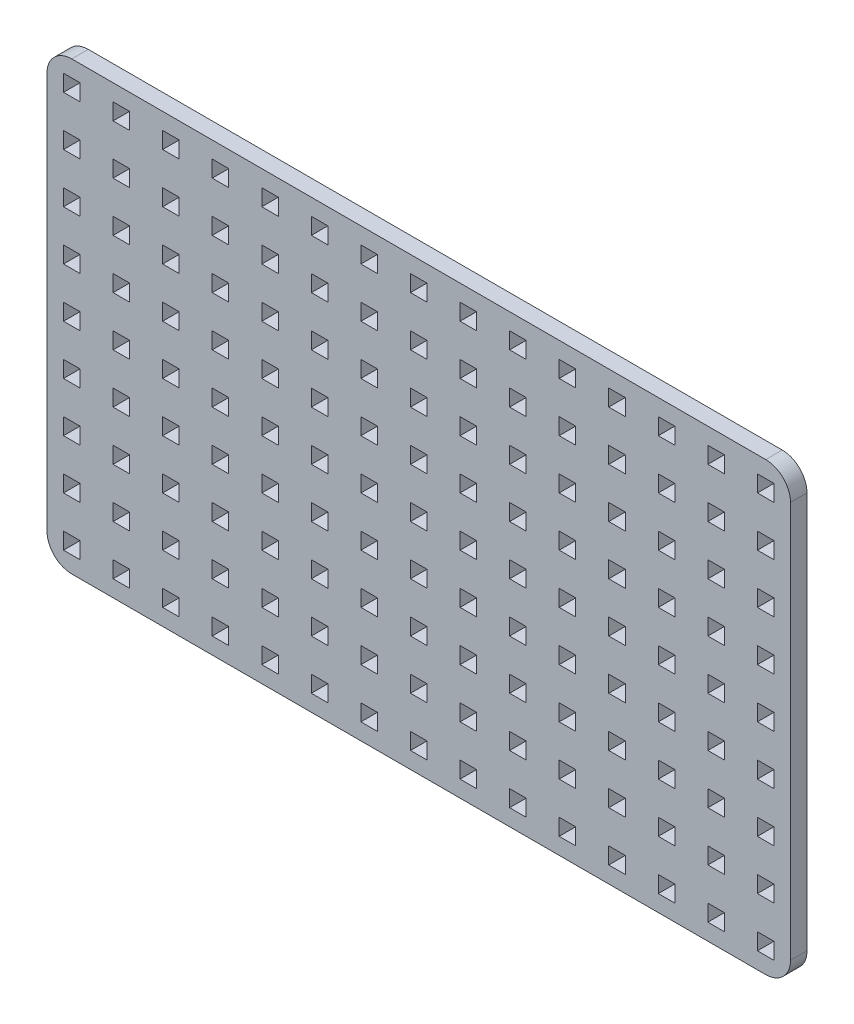
SolidWorks part; units mm, degrees
ref_plane "Alzado" through (0, 0, 0) normal (0, 0, 1) x (1, 0, 0)
ref_plane "Planta" through (0, 0, 0) normal (0, 1, 0) x (1, 0, 0)
ref_plane "Vista lateral" through (0, 0, 0) normal (1, 0, 0) x (0, 0, -1)
sketch "Model" plane through (0, 0, 0) normal (0, 0, 1) x (1, 0, 0)
  line L0 (12.5036, 293.2506) -> (12.5036, 290.2506)
  line L1 (15.5036, 293.2506) -> (12.5036, 293.2506)
  line L2 (15.5036, 290.2506) -> (15.5036, 293.2506)
  line L3 (12.5036, 290.2506) -> (15.5036, 290.2506)
  line L4 (21.5036, 293.2506) -> (21.5036, 290.2506)
  line L5 (24.5036, 293.2506) -> (21.5036, 293.2506)
  line L6 (24.5036, 290.2506) -> (24.5036, 293.2506)
  line L7 (21.5036, 290.2506) -> (24.5036, 290.2506)
  line L8 (30.5036, 293.2506) -> (30.5036, 290.2506)
  line L9 (33.5036, 293.2506) -> (30.5036, 293.2506)
  line L10 (33.5036, 290.2506) -> (33.5036, 293.2506)
  line L11 (30.5036, 290.2506) -> (33.5036, 290.2506)
  line L12 (39.5036, 293.2506) -> (39.5036, 290.2506)
  line L13 (42.5036, 293.2506) -> (39.5036, 293.2506)
  line L14 (42.5036, 290.2506) -> (42.5036, 293.2506)
  line L15 (39.5036, 290.2506) -> (42.5036, 290.2506)
  line L16 (48.5036, 293.2506) -> (48.5036, 290.2506)
  line L17 (51.5036, 293.2506) -> (48.5036, 293.2506)
  line L18 (51.5036, 290.2506) -> (51.5036, 293.2506)
  line L19 (48.5036, 290.2506) -> (51.5036, 290.2506)
  line L20 (57.5036, 293.2506) -> (57.5036, 290.2506)
  line L21 (60.5036, 293.2506) -> (57.5036, 293.2506)
  line L22 (60.5036, 290.2506) -> (60.5036, 293.2506)
  line L23 (57.5036, 290.2506) -> (60.5036, 290.2506)
  line L24 (66.5036, 293.2506) -> (66.5036, 290.2506)
  line L25 (69.5036, 293.2506) -> (66.5036, 293.2506)
  line L26 (69.5036, 290.2506) -> (69.5036, 293.2506)
  line L27 (66.5036, 290.2506) -> (69.5036, 290.2506)
  line L28 (75.5036, 293.2506) -> (75.5036, 290.2506)
  line L29 (78.5036, 293.2506) -> (75.5036, 293.2506)
  line L30 (78.5036, 290.2506) -> (78.5036, 293.2506)
  line L31 (75.5036, 290.2506) -> (78.5036, 290.2506)
  line L32 (84.5036, 293.2506) -> (84.5036, 290.2506)
  line L33 (87.5036, 293.2506) -> (84.5036, 293.2506)
  line L34 (87.5036, 290.2506) -> (87.5036, 293.2506)
  line L35 (84.5036, 290.2506) -> (87.5036, 290.2506)
  line L36 (93.5036, 293.2506) -> (93.5036, 290.2506)
  line L37 (96.5036, 293.2506) -> (93.5036, 293.2506)
  line L38 (96.5036, 290.2506) -> (96.5036, 293.2506)
  line L39 (93.5036, 290.2506) -> (96.5036, 290.2506)
  line L40 (102.5036, 293.2506) -> (102.5036, 290.2506)
  line L41 (105.5036, 293.2506) -> (102.5036, 293.2506)
  line L42 (105.5036, 290.2506) -> (105.5036, 293.2506)
  line L43 (102.5036, 290.2506) -> (105.5036, 290.2506)
  line L44 (111.5036, 293.2506) -> (111.5036, 290.2506)
  line L45 (114.5036, 293.2506) -> (111.5036, 293.2506)
  line L46 (114.5036, 290.2506) -> (114.5036, 293.2506)
  line L47 (111.5036, 290.2506) -> (114.5036, 290.2506)
  line L48 (120.5036, 293.2506) -> (120.5036, 290.2506)
  line L49 (123.5036, 293.2506) -> (120.5036, 293.2506)
  line L50 (123.5036, 290.2506) -> (123.5036, 293.2506)
  line L51 (120.5036, 290.2506) -> (123.5036, 290.2506)
  line L52 (129.5036, 293.2506) -> (129.5036, 290.2506)
  line L53 (132.5036, 293.2506) -> (129.5036, 293.2506)
  line L54 (132.5036, 290.2506) -> (132.5036, 293.2506)
  line L55 (129.5036, 290.2506) -> (132.5036, 290.2506)
  line L56 (138.5036, 293.2506) -> (138.5036, 290.2506)
  line L57 (141.5036, 293.2506) -> (138.5036, 293.2506)
  line L58 (141.5036, 290.2506) -> (141.5036, 293.2506)
  line L59 (138.5036, 290.2506) -> (141.5036, 290.2506)
  line L60 (12.5036, 284.2506) -> (12.5036, 281.2506)
  line L61 (15.5036, 284.2506) -> (12.5036, 284.2506)
  line L62 (15.5036, 281.2506) -> (15.5036, 284.2506)
  line L63 (12.5036, 281.2506) -> (15.5036, 281.2506)
  line L64 (21.5036, 284.2506) -> (21.5036, 281.2506)
  line L65 (24.5036, 284.2506) -> (21.5036, 284.2506)
  line L66 (24.5036, 281.2506) -> (24.5036, 284.2506)
  line L67 (21.5036, 281.2506) -> (24.5036, 281.2506)
  line L68 (30.5036, 284.2506) -> (30.5036, 281.2506)
  line L69 (33.5036, 284.2506) -> (30.5036, 284.2506)
  line L70 (33.5036, 281.2506) -> (33.5036, 284.2506)
  line L71 (30.5036, 281.2506) -> (33.5036, 281.2506)
  line L72 (39.5036, 284.2506) -> (39.5036, 281.2506)
  line L73 (42.5036, 284.2506) -> (39.5036, 284.2506)
  line L74 (42.5036, 281.2506) -> (42.5036, 284.2506)
  line L75 (39.5036, 281.2506) -> (42.5036, 281.2506)
  line L76 (48.5036, 284.2506) -> (48.5036, 281.2506)
  line L77 (51.5036, 284.2506) -> (48.5036, 284.2506)
  line L78 (51.5036, 281.2506) -> (51.5036, 284.2506)
  line L79 (48.5036, 281.2506) -> (51.5036, 281.2506)
  line L80 (57.5036, 284.2506) -> (57.5036, 281.2506)
  line L81 (60.5036, 284.2506) -> (57.5036, 284.2506)
  line L82 (60.5036, 281.2506) -> (60.5036, 284.2506)
  line L83 (57.5036, 281.2506) -> (60.5036, 281.2506)
  line L84 (66.5036, 284.2506) -> (66.5036, 281.2506)
  line L85 (69.5036, 284.2506) -> (66.5036, 284.2506)
  line L86 (69.5036, 281.2506) -> (69.5036, 284.2506)
  line L87 (66.5036, 281.2506) -> (69.5036, 281.2506)
  line L88 (75.5036, 284.2506) -> (75.5036, 281.2506)
  line L89 (78.5036, 284.2506) -> (75.5036, 284.2506)
  line L90 (78.5036, 281.2506) -> (78.5036, 284.2506)
  line L91 (75.5036, 281.2506) -> (78.5036, 281.2506)
  line L92 (84.5036, 284.2506) -> (84.5036, 281.2506)
  line L93 (87.5036, 284.2506) -> (84.5036, 284.2506)
  line L94 (87.5036, 281.2506) -> (87.5036, 284.2506)
  line L95 (84.5036, 281.2506) -> (87.5036, 281.2506)
  line L96 (93.5036, 284.2506) -> (93.5036, 281.2506)
  line L97 (96.5036, 284.2506) -> (93.5036, 284.2506)
  line L98 (96.5036, 281.2506) -> (96.5036, 284.2506)
  line L99 (93.5036, 281.2506) -> (96.5036, 281.2506)
  line L100 (102.5036, 284.2506) -> (102.5036, 281.2506)
  line L101 (105.5036, 284.2506) -> (102.5036, 284.2506)
  line L102 (105.5036, 281.2506) -> (105.5036, 284.2506)
  line L103 (102.5036, 281.2506) -> (105.5036, 281.2506)
  line L104 (111.5036, 284.2506) -> (111.5036, 281.2506)
  line L105 (114.5036, 284.2506) -> (111.5036, 284.2506)
  line L106 (114.5036, 281.2506) -> (114.5036, 284.2506)
  line L107 (111.5036, 281.2506) -> (114.5036, 281.2506)
  line L108 (120.5036, 284.2506) -> (120.5036, 281.2506)
  line L109 (123.5036, 284.2506) -> (120.5036, 284.2506)
  line L110 (123.5036, 281.2506) -> (123.5036, 284.2506)
  line L111 (120.5036, 281.2506) -> (123.5036, 281.2506)
  line L112 (129.5036, 284.2506) -> (129.5036, 281.2506)
  line L113 (132.5036, 284.2506) -> (129.5036, 284.2506)
  line L114 (132.5036, 281.2506) -> (132.5036, 284.2506)
  line L115 (129.5036, 281.2506) -> (132.5036, 281.2506)
  line L116 (138.5036, 284.2506) -> (138.5036, 281.2506)
  line L117 (141.5036, 284.2506) -> (138.5036, 284.2506)
  line L118 (141.5036, 281.2506) -> (141.5036, 284.2506)
  line L119 (138.5036, 281.2506) -> (141.5036, 281.2506)
  line L120 (12.5036, 275.2506) -> (12.5036, 272.2506)
  line L121 (15.5036, 275.2506) -> (12.5036, 275.2506)
  line L122 (15.5036, 272.2506) -> (15.5036, 275.2506)
  line L123 (12.5036, 272.2506) -> (15.5036, 272.2506)
  line L124 (21.5036, 275.2506) -> (21.5036, 272.2506)
  line L125 (24.5036, 275.2506) -> (21.5036, 275.2506)
  line L126 (24.5036, 272.2506) -> (24.5036, 275.2506)
  line L127 (21.5036, 272.2506) -> (24.5036, 272.2506)
  line L128 (30.5036, 275.2506) -> (30.5036, 272.2506)
  line L129 (33.5036, 275.2506) -> (30.5036, 275.2506)
  line L130 (33.5036, 272.2506) -> (33.5036, 275.2506)
  line L131 (30.5036, 272.2506) -> (33.5036, 272.2506)
  line L132 (39.5036, 275.2506) -> (39.5036, 272.2506)
  line L133 (42.5036, 275.2506) -> (39.5036, 275.2506)
  line L134 (42.5036, 272.2506) -> (42.5036, 275.2506)
  line L135 (39.5036, 272.2506) -> (42.5036, 272.2506)
  line L136 (48.5036, 275.2506) -> (48.5036, 272.2506)
  line L137 (51.5036, 275.2506) -> (48.5036, 275.2506)
  line L138 (51.5036, 272.2506) -> (51.5036, 275.2506)
  line L139 (48.5036, 272.2506) -> (51.5036, 272.2506)
  line L140 (57.5036, 275.2506) -> (57.5036, 272.2506)
  line L141 (60.5036, 275.2506) -> (57.5036, 275.2506)
  line L142 (60.5036, 272.2506) -> (60.5036, 275.2506)
  line L143 (57.5036, 272.2506) -> (60.5036, 272.2506)
  line L144 (66.5036, 275.2506) -> (66.5036, 272.2506)
  line L145 (69.5036, 275.2506) -> (66.5036, 275.2506)
  line L146 (69.5036, 272.2506) -> (69.5036, 275.2506)
  line L147 (66.5036, 272.2506) -> (69.5036, 272.2506)
  line L148 (75.5036, 275.2506) -> (75.5036, 272.2506)
  line L149 (78.5036, 275.2506) -> (75.5036, 275.2506)
  line L150 (78.5036, 272.2506) -> (78.5036, 275.2506)
  line L151 (75.5036, 272.2506) -> (78.5036, 272.2506)
  line L152 (84.5036, 275.2506) -> (84.5036, 272.2506)
  line L153 (87.5036, 275.2506) -> (84.5036, 275.2506)
  line L154 (87.5036, 272.2506) -> (87.5036, 275.2506)
  line L155 (84.5036, 272.2506) -> (87.5036, 272.2506)
  line L156 (93.5036, 275.2506) -> (93.5036, 272.2506)
  line L157 (96.5036, 275.2506) -> (93.5036, 275.2506)
  line L158 (96.5036, 272.2506) -> (96.5036, 275.2506)
  line L159 (93.5036, 272.2506) -> (96.5036, 272.2506)
  line L160 (102.5036, 275.2506) -> (102.5036, 272.2506)
  line L161 (105.5036, 275.2506) -> (102.5036, 275.2506)
  line L162 (105.5036, 272.2506) -> (105.5036, 275.2506)
  line L163 (102.5036, 272.2506) -> (105.5036, 272.2506)
  line L164 (111.5036, 275.2506) -> (111.5036, 272.2506)
  line L165 (114.5036, 275.2506) -> (111.5036, 275.2506)
  line L166 (114.5036, 272.2506) -> (114.5036, 275.2506)
  line L167 (111.5036, 272.2506) -> (114.5036, 272.2506)
  line L168 (120.5036, 275.2506) -> (120.5036, 272.2506)
  line L169 (123.5036, 275.2506) -> (120.5036, 275.2506)
  line L170 (123.5036, 272.2506) -> (123.5036, 275.2506)
  line L171 (120.5036, 272.2506) -> (123.5036, 272.2506)
  line L172 (129.5036, 275.2506) -> (129.5036, 272.2506)
  line L173 (132.5036, 275.2506) -> (129.5036, 275.2506)
  line L174 (132.5036, 272.2506) -> (132.5036, 275.2506)
  line L175 (129.5036, 272.2506) -> (132.5036, 272.2506)
  line L176 (138.5036, 275.2506) -> (138.5036, 272.2506)
  line L177 (141.5036, 275.2506) -> (138.5036, 275.2506)
  line L178 (141.5036, 272.2506) -> (141.5036, 275.2506)
  line L179 (138.5036, 272.2506) -> (141.5036, 272.2506)
  line L180 (12.5036, 266.2506) -> (12.5036, 263.2506)
  line L181 (15.5036, 266.2506) -> (12.5036, 266.2506)
  line L182 (15.5036, 263.2506) -> (15.5036, 266.2506)
  line L183 (12.5036, 263.2506) -> (15.5036, 263.2506)
  line L184 (21.5036, 266.2506) -> (21.5036, 263.2506)
  line L185 (24.5036, 266.2506) -> (21.5036, 266.2506)
  line L186 (24.5036, 263.2506) -> (24.5036, 266.2506)
  line L187 (21.5036, 263.2506) -> (24.5036, 263.2506)
  line L188 (30.5036, 266.2506) -> (30.5036, 263.2506)
  line L189 (33.5036, 266.2506) -> (30.5036, 266.2506)
  line L190 (33.5036, 263.2506) -> (33.5036, 266.2506)
  line L191 (30.5036, 263.2506) -> (33.5036, 263.2506)
  line L192 (39.5036, 266.2506) -> (39.5036, 263.2506)
  line L193 (42.5036, 266.2506) -> (39.5036, 266.2506)
  line L194 (42.5036, 263.2506) -> (42.5036, 266.2506)
  line L195 (39.5036, 263.2506) -> (42.5036, 263.2506)
  line L196 (48.5036, 266.2506) -> (48.5036, 263.2506)
  line L197 (51.5036, 266.2506) -> (48.5036, 266.2506)
  line L198 (51.5036, 263.2506) -> (51.5036, 266.2506)
  line L199 (48.5036, 263.2506) -> (51.5036, 263.2506)
  line L200 (57.5036, 266.2506) -> (57.5036, 263.2506)
  line L201 (60.5036, 266.2506) -> (57.5036, 266.2506)
  line L202 (60.5036, 263.2506) -> (60.5036, 266.2506)
  line L203 (57.5036, 263.2506) -> (60.5036, 263.2506)
  line L204 (66.5036, 266.2506) -> (66.5036, 263.2506)
  line L205 (69.5036, 266.2506) -> (66.5036, 266.2506)
  line L206 (69.5036, 263.2506) -> (69.5036, 266.2506)
  line L207 (66.5036, 263.2506) -> (69.5036, 263.2506)
  line L208 (75.5036, 266.2506) -> (75.5036, 263.2506)
  line L209 (78.5036, 266.2506) -> (75.5036, 266.2506)
  line L210 (78.5036, 263.2506) -> (78.5036, 266.2506)
  line L211 (75.5036, 263.2506) -> (78.5036, 263.2506)
  line L212 (84.5036, 266.2506) -> (84.5036, 263.2506)
  line L213 (87.5036, 266.2506) -> (84.5036, 266.2506)
  line L214 (87.5036, 263.2506) -> (87.5036, 266.2506)
  line L215 (84.5036, 263.2506) -> (87.5036, 263.2506)
  line L216 (93.5036, 266.2506) -> (93.5036, 263.2506)
  line L217 (96.5036, 266.2506) -> (93.5036, 266.2506)
  line L218 (96.5036, 263.2506) -> (96.5036, 266.2506)
  line L219 (93.5036, 263.2506) -> (96.5036, 263.2506)
  line L220 (102.5036, 266.2506) -> (102.5036, 263.2506)
  line L221 (105.5036, 266.2506) -> (102.5036, 266.2506)
  line L222 (105.5036, 263.2506) -> (105.5036, 266.2506)
  line L223 (102.5036, 263.2506) -> (105.5036, 263.2506)
  line L224 (111.5036, 266.2506) -> (111.5036, 263.2506)
  line L225 (114.5036, 266.2506) -> (111.5036, 266.2506)
  line L226 (114.5036, 263.2506) -> (114.5036, 266.2506)
  line L227 (111.5036, 263.2506) -> (114.5036, 263.2506)
  line L228 (120.5036, 266.2506) -> (120.5036, 263.2506)
  line L229 (123.5036, 266.2506) -> (120.5036, 266.2506)
  line L230 (123.5036, 263.2506) -> (123.5036, 266.2506)
  line L231 (120.5036, 263.2506) -> (123.5036, 263.2506)
  line L232 (129.5036, 266.2506) -> (129.5036, 263.2506)
  line L233 (132.5036, 266.2506) -> (129.5036, 266.2506)
  line L234 (132.5036, 263.2506) -> (132.5036, 266.2506)
  line L235 (129.5036, 263.2506) -> (132.5036, 263.2506)
  line L236 (138.5036, 266.2506) -> (138.5036, 263.2506)
  line L237 (141.5036, 266.2506) -> (138.5036, 266.2506)
  line L238 (141.5036, 263.2506) -> (141.5036, 266.2506)
  line L239 (138.5036, 263.2506) -> (141.5036, 263.2506)
  line L240 (12.5036, 257.2506) -> (12.5036, 254.2506)
  line L241 (15.5036, 257.2506) -> (12.5036, 257.2506)
  line L242 (15.5036, 254.2506) -> (15.5036, 257.2506)
  line L243 (12.5036, 254.2506) -> (15.5036, 254.2506)
  line L244 (21.5036, 257.2506) -> (21.5036, 254.2506)
  line L245 (24.5036, 257.2506) -> (21.5036, 257.2506)
  line L246 (24.5036, 254.2506) -> (24.5036, 257.2506)
  line L247 (21.5036, 254.2506) -> (24.5036, 254.2506)
  line L248 (30.5036, 257.2506) -> (30.5036, 254.2506)
  line L249 (33.5036, 257.2506) -> (30.5036, 257.2506)
  line L250 (33.5036, 254.2506) -> (33.5036, 257.2506)
  line L251 (30.5036, 254.2506) -> (33.5036, 254.2506)
  line L252 (39.5036, 257.2506) -> (39.5036, 254.2506)
  line L253 (42.5036, 257.2506) -> (39.5036, 257.2506)
  line L254 (42.5036, 254.2506) -> (42.5036, 257.2506)
  line L255 (39.5036, 254.2506) -> (42.5036, 254.2506)
  line L256 (48.5036, 257.2506) -> (48.5036, 254.2506)
  line L257 (51.5036, 257.2506) -> (48.5036, 257.2506)
  line L258 (51.5036, 254.2506) -> (51.5036, 257.2506)
  line L259 (48.5036, 254.2506) -> (51.5036, 254.2506)
  line L260 (57.5036, 257.2506) -> (57.5036, 254.2506)
  line L261 (60.5036, 257.2506) -> (57.5036, 257.2506)
  line L262 (60.5036, 254.2506) -> (60.5036, 257.2506)
  line L263 (57.5036, 254.2506) -> (60.5036, 254.2506)
  line L264 (66.5036, 257.2506) -> (66.5036, 254.2506)
  line L265 (69.5036, 257.2506) -> (66.5036, 257.2506)
  line L266 (69.5036, 254.2506) -> (69.5036, 257.2506)
  line L267 (66.5036, 254.2506) -> (69.5036, 254.2506)
  line L268 (75.5036, 257.2506) -> (75.5036, 254.2506)
  line L269 (78.5036, 257.2506) -> (75.5036, 257.2506)
  line L270 (78.5036, 254.2506) -> (78.5036, 257.2506)
  line L271 (75.5036, 254.2506) -> (78.5036, 254.2506)
  line L272 (84.5036, 257.2506) -> (84.5036, 254.2506)
  line L273 (87.5036, 257.2506) -> (84.5036, 257.2506)
  line L274 (87.5036, 254.2506) -> (87.5036, 257.2506)
  line L275 (84.5036, 254.2506) -> (87.5036, 254.2506)
  line L276 (93.5036, 257.2506) -> (93.5036, 254.2506)
  line L277 (96.5036, 257.2506) -> (93.5036, 257.2506)
  line L278 (96.5036, 254.2506) -> (96.5036, 257.2506)
  line L279 (93.5036, 254.2506) -> (96.5036, 254.2506)
  line L280 (102.5036, 257.2506) -> (102.5036, 254.2506)
  line L281 (105.5036, 257.2506) -> (102.5036, 257.2506)
  line L282 (105.5036, 254.2506) -> (105.5036, 257.2506)
  line L283 (102.5036, 254.2506) -> (105.5036, 254.2506)
  line L284 (111.5036, 257.2506) -> (111.5036, 254.2506)
  line L285 (114.5036, 257.2506) -> (111.5036, 257.2506)
  line L286 (114.5036, 254.2506) -> (114.5036, 257.2506)
  line L287 (111.5036, 254.2506) -> (114.5036, 254.2506)
  line L288 (120.5036, 257.2506) -> (120.5036, 254.2506)
  line L289 (123.5036, 257.2506) -> (120.5036, 257.2506)
  line L290 (123.5036, 254.2506) -> (123.5036, 257.2506)
  line L291 (120.5036, 254.2506) -> (123.5036, 254.2506)
  line L292 (129.5036, 257.2506) -> (129.5036, 254.2506)
  line L293 (132.5036, 257.2506) -> (129.5036, 257.2506)
  line L294 (132.5036, 254.2506) -> (132.5036, 257.2506)
  line L295 (129.5036, 254.2506) -> (132.5036, 254.2506)
  line L296 (138.5036, 257.2506) -> (138.5036, 254.2506)
  line L297 (141.5036, 257.2506) -> (138.5036, 257.2506)
  line L298 (141.5036, 254.2506) -> (141.5036, 257.2506)
  line L299 (138.5036, 254.2506) -> (141.5036, 254.2506)
  line L300 (12.5036, 248.2506) -> (12.5036, 245.2506)
  line L301 (15.5036, 248.2506) -> (12.5036, 248.2506)
  line L302 (15.5036, 245.2506) -> (15.5036, 248.2506)
  line L303 (12.5036, 245.2506) -> (15.5036, 245.2506)
  line L304 (21.5036, 248.2506) -> (21.5036, 245.2506)
  line L305 (24.5036, 248.2506) -> (21.5036, 248.2506)
  line L306 (24.5036, 245.2506) -> (24.5036, 248.2506)
  line L307 (21.5036, 245.2506) -> (24.5036, 245.2506)
  line L308 (30.5036, 248.2506) -> (30.5036, 245.2506)
  line L309 (33.5036, 248.2506) -> (30.5036, 248.2506)
  line L310 (33.5036, 245.2506) -> (33.5036, 248.2506)
  line L311 (30.5036, 245.2506) -> (33.5036, 245.2506)
  line L312 (39.5036, 248.2506) -> (39.5036, 245.2506)
  line L313 (42.5036, 248.2506) -> (39.5036, 248.2506)
  line L314 (42.5036, 245.2506) -> (42.5036, 248.2506)
  line L315 (39.5036, 245.2506) -> (42.5036, 245.2506)
  line L316 (48.5036, 248.2506) -> (48.5036, 245.2506)
  line L317 (51.5036, 248.2506) -> (48.5036, 248.2506)
  line L318 (51.5036, 245.2506) -> (51.5036, 248.2506)
  line L319 (48.5036, 245.2506) -> (51.5036, 245.2506)
  line L320 (57.5036, 248.2506) -> (57.5036, 245.2506)
  line L321 (60.5036, 248.2506) -> (57.5036, 248.2506)
  line L322 (60.5036, 245.2506) -> (60.5036, 248.2506)
  line L323 (57.5036, 245.2506) -> (60.5036, 245.2506)
  line L324 (66.5036, 248.2506) -> (66.5036, 245.2506)
  line L325 (69.5036, 248.2506) -> (66.5036, 248.2506)
  line L326 (69.5036, 245.2506) -> (69.5036, 248.2506)
  line L327 (66.5036, 245.2506) -> (69.5036, 245.2506)
  line L328 (75.5036, 248.2506) -> (75.5036, 245.2506)
  line L329 (78.5036, 248.2506) -> (75.5036, 248.2506)
  line L330 (78.5036, 245.2506) -> (78.5036, 248.2506)
  line L331 (75.5036, 245.2506) -> (78.5036, 245.2506)
  line L332 (84.5036, 248.2506) -> (84.5036, 245.2506)
  line L333 (87.5036, 248.2506) -> (84.5036, 248.2506)
  line L334 (87.5036, 245.2506) -> (87.5036, 248.2506)
  line L335 (84.5036, 245.2506) -> (87.5036, 245.2506)
  line L336 (93.5036, 248.2506) -> (93.5036, 245.2506)
  line L337 (96.5036, 248.2506) -> (93.5036, 248.2506)
  line L338 (96.5036, 245.2506) -> (96.5036, 248.2506)
  line L339 (93.5036, 245.2506) -> (96.5036, 245.2506)
  line L340 (102.5036, 248.2506) -> (102.5036, 245.2506)
  line L341 (105.5036, 248.2506) -> (102.5036, 248.2506)
  line L342 (105.5036, 245.2506) -> (105.5036, 248.2506)
  line L343 (102.5036, 245.2506) -> (105.5036, 245.2506)
  line L344 (111.5036, 248.2506) -> (111.5036, 245.2506)
  line L345 (114.5036, 248.2506) -> (111.5036, 248.2506)
  line L346 (114.5036, 245.2506) -> (114.5036, 248.2506)
  line L347 (111.5036, 245.2506) -> (114.5036, 245.2506)
  line L348 (120.5036, 248.2506) -> (120.5036, 245.2506)
  line L349 (123.5036, 248.2506) -> (120.5036, 248.2506)
  line L350 (123.5036, 245.2506) -> (123.5036, 248.2506)
  line L351 (120.5036, 245.2506) -> (123.5036, 245.2506)
  line L352 (129.5036, 248.2506) -> (129.5036, 245.2506)
  line L353 (132.5036, 248.2506) -> (129.5036, 248.2506)
  line L354 (132.5036, 245.2506) -> (132.5036, 248.2506)
  line L355 (129.5036, 245.2506) -> (132.5036, 245.2506)
  line L356 (138.5036, 248.2506) -> (138.5036, 245.2506)
  line L357 (141.5036, 248.2506) -> (138.5036, 248.2506)
  line L358 (141.5036, 245.2506) -> (141.5036, 248.2506)
  line L359 (138.5036, 245.2506) -> (141.5036, 245.2506)
  line L360 (12.5036, 239.2506) -> (12.5036, 236.2506)
  line L361 (15.5036, 239.2506) -> (12.5036, 239.2506)
  line L362 (15.5036, 236.2506) -> (15.5036, 239.2506)
  line L363 (12.5036, 236.2506) -> (15.5036, 236.2506)
  line L364 (21.5036, 239.2506) -> (21.5036, 236.2506)
  line L365 (24.5036, 239.2506) -> (21.5036, 239.2506)
  line L366 (24.5036, 236.2506) -> (24.5036, 239.2506)
  line L367 (21.5036, 236.2506) -> (24.5036, 236.2506)
  line L368 (30.5036, 239.2506) -> (30.5036, 236.2506)
  line L369 (33.5036, 239.2506) -> (30.5036, 239.2506)
  line L370 (33.5036, 236.2506) -> (33.5036, 239.2506)
  line L371 (30.5036, 236.2506) -> (33.5036, 236.2506)
  line L372 (39.5036, 239.2506) -> (39.5036, 236.2506)
  line L373 (42.5036, 239.2506) -> (39.5036, 239.2506)
  line L374 (42.5036, 236.2506) -> (42.5036, 239.2506)
  line L375 (39.5036, 236.2506) -> (42.5036, 236.2506)
  line L376 (48.5036, 239.2506) -> (48.5036, 236.2506)
  line L377 (51.5036, 239.2506) -> (48.5036, 239.2506)
  line L378 (51.5036, 236.2506) -> (51.5036, 239.2506)
  line L379 (48.5036, 236.2506) -> (51.5036, 236.2506)
  line L380 (57.5036, 239.2506) -> (57.5036, 236.2506)
  line L381 (60.5036, 239.2506) -> (57.5036, 239.2506)
  line L382 (60.5036, 236.2506) -> (60.5036, 239.2506)
  line L383 (57.5036, 236.2506) -> (60.5036, 236.2506)
  line L384 (66.5036, 239.2506) -> (66.5036, 236.2506)
  line L385 (69.5036, 239.2506) -> (66.5036, 239.2506)
  line L386 (69.5036, 236.2506) -> (69.5036, 239.2506)
  line L387 (66.5036, 236.2506) -> (69.5036, 236.2506)
  line L388 (75.5036, 239.2506) -> (75.5036, 236.2506)
  line L389 (78.5036, 239.2506) -> (75.5036, 239.2506)
  line L390 (78.5036, 236.2506) -> (78.5036, 239.2506)
  line L391 (75.5036, 236.2506) -> (78.5036, 236.2506)
  line L392 (84.5036, 239.2506) -> (84.5036, 236.2506)
  line L393 (87.5036, 239.2506) -> (84.5036, 239.2506)
  line L394 (87.5036, 236.2506) -> (87.5036, 239.2506)
  line L395 (84.5036, 236.2506) -> (87.5036, 236.2506)
  line L396 (93.5036, 239.2506) -> (93.5036, 236.2506)
  line L397 (96.5036, 239.2506) -> (93.5036, 239.2506)
  line L398 (96.5036, 236.2506) -> (96.5036, 239.2506)
  line L399 (93.5036, 236.2506) -> (96.5036, 236.2506)
  line L400 (102.5036, 239.2506) -> (102.5036, 236.2506)
  line L401 (105.5036, 239.2506) -> (102.5036, 239.2506)
  line L402 (105.5036, 236.2506) -> (105.5036, 239.2506)
  line L403 (102.5036, 236.2506) -> (105.5036, 236.2506)
  line L404 (111.5036, 239.2506) -> (111.5036, 236.2506)
  line L405 (114.5036, 239.2506) -> (111.5036, 239.2506)
  line L406 (114.5036, 236.2506) -> (114.5036, 239.2506)
  line L407 (111.5036, 236.2506) -> (114.5036, 236.2506)
  line L408 (120.5036, 239.2506) -> (120.5036, 236.2506)
  line L409 (123.5036, 239.2506) -> (120.5036, 239.2506)
  line L410 (123.5036, 236.2506) -> (123.5036, 239.2506)
  line L411 (120.5036, 236.2506) -> (123.5036, 236.2506)
  line L412 (129.5036, 239.2506) -> (129.5036, 236.2506)
  line L413 (132.5036, 239.2506) -> (129.5036, 239.2506)
  line L414 (132.5036, 236.2506) -> (132.5036, 239.2506)
  line L415 (129.5036, 236.2506) -> (132.5036, 236.2506)
  line L416 (138.5036, 239.2506) -> (138.5036, 236.2506)
  line L417 (141.5036, 239.2506) -> (138.5036, 239.2506)
  line L418 (141.5036, 236.2506) -> (141.5036, 239.2506)
  line L419 (138.5036, 236.2506) -> (141.5036, 236.2506)
  line L420 (12.5036, 230.2506) -> (12.5036, 227.2506)
  line L421 (15.5036, 230.2506) -> (12.5036, 230.2506)
  line L422 (15.5036, 227.2506) -> (15.5036, 230.2506)
  line L423 (12.5036, 227.2506) -> (15.5036, 227.2506)
  line L424 (21.5036, 230.2506) -> (21.5036, 227.2506)
  line L425 (24.5036, 230.2506) -> (21.5036, 230.2506)
  line L426 (24.5036, 227.2506) -> (24.5036, 230.2506)
  line L427 (21.5036, 227.2506) -> (24.5036, 227.2506)
  line L428 (30.5036, 230.2506) -> (30.5036, 227.2506)
  line L429 (33.5036, 230.2506) -> (30.5036, 230.2506)
  line L430 (33.5036, 227.2506) -> (33.5036, 230.2506)
  line L431 (30.5036, 227.2506) -> (33.5036, 227.2506)
  line L432 (39.5036, 230.2506) -> (39.5036, 227.2506)
  line L433 (42.5036, 230.2506) -> (39.5036, 230.2506)
  line L434 (42.5036, 227.2506) -> (42.5036, 230.2506)
  line L435 (39.5036, 227.2506) -> (42.5036, 227.2506)
  line L436 (48.5036, 230.2506) -> (48.5036, 227.2506)
  line L437 (51.5036, 230.2506) -> (48.5036, 230.2506)
  line L438 (51.5036, 227.2506) -> (51.5036, 230.2506)
  line L439 (48.5036, 227.2506) -> (51.5036, 227.2506)
  line L440 (57.5036, 230.2506) -> (57.5036, 227.2506)
  line L441 (60.5036, 230.2506) -> (57.5036, 230.2506)
  line L442 (60.5036, 227.2506) -> (60.5036, 230.2506)
  line L443 (57.5036, 227.2506) -> (60.5036, 227.2506)
  line L444 (66.5036, 230.2506) -> (66.5036, 227.2506)
  line L445 (69.5036, 230.2506) -> (66.5036, 230.2506)
  line L446 (69.5036, 227.2506) -> (69.5036, 230.2506)
  line L447 (66.5036, 227.2506) -> (69.5036, 227.2506)
  line L448 (75.5036, 230.2506) -> (75.5036, 227.2506)
  line L449 (78.5036, 230.2506) -> (75.5036, 230.2506)
  line L450 (78.5036, 227.2506) -> (78.5036, 230.2506)
  line L451 (75.5036, 227.2506) -> (78.5036, 227.2506)
  line L452 (84.5036, 230.2506) -> (84.5036, 227.2506)
  line L453 (87.5036, 230.2506) -> (84.5036, 230.2506)
  line L454 (87.5036, 227.2506) -> (87.5036, 230.2506)
  line L455 (84.5036, 227.2506) -> (87.5036, 227.2506)
  line L456 (93.5036, 230.2506) -> (93.5036, 227.2506)
  line L457 (96.5036, 230.2506) -> (93.5036, 230.2506)
  line L458 (96.5036, 227.2506) -> (96.5036, 230.2506)
  line L459 (93.5036, 227.2506) -> (96.5036, 227.2506)
  line L460 (102.5036, 230.2506) -> (102.5036, 227.2506)
  line L461 (105.5036, 230.2506) -> (102.5036, 230.2506)
  line L462 (105.5036, 227.2506) -> (105.5036, 230.2506)
  line L463 (102.5036, 227.2506) -> (105.5036, 227.2506)
  line L464 (111.5036, 230.2506) -> (111.5036, 227.2506)
  line L465 (114.5036, 230.2506) -> (111.5036, 230.2506)
  line L466 (114.5036, 227.2506) -> (114.5036, 230.2506)
  line L467 (111.5036, 227.2506) -> (114.5036, 227.2506)
  line L468 (120.5036, 230.2506) -> (120.5036, 227.2506)
  line L469 (123.5036, 230.2506) -> (120.5036, 230.2506)
  line L470 (123.5036, 227.2506) -> (123.5036, 230.2506)
  line L471 (120.5036, 227.2506) -> (123.5036, 227.2506)
  line L472 (129.5036, 230.2506) -> (129.5036, 227.2506)
  line L473 (132.5036, 230.2506) -> (129.5036, 230.2506)
  line L474 (132.5036, 227.2506) -> (132.5036, 230.2506)
  line L475 (129.5036, 227.2506) -> (132.5036, 227.2506)
  line L476 (138.5036, 230.2506) -> (138.5036, 227.2506)
  line L477 (141.5036, 230.2506) -> (138.5036, 230.2506)
  line L478 (141.5036, 227.2506) -> (141.5036, 230.2506)
  line L479 (138.5036, 227.2506) -> (141.5036, 227.2506)
  line L480 (12.5036, 221.2506) -> (12.5036, 218.2506)
  line L481 (15.5036, 221.2506) -> (12.5036, 221.2506)
  line L482 (15.5036, 218.2506) -> (15.5036, 221.2506)
  line L483 (12.5036, 218.2506) -> (15.5036, 218.2506)
  line L484 (21.5036, 221.2506) -> (21.5036, 218.2506)
  line L485 (24.5036, 221.2506) -> (21.5036, 221.2506)
  line L486 (24.5036, 218.2506) -> (24.5036, 221.2506)
  line L487 (21.5036, 218.2506) -> (24.5036, 218.2506)
  line L488 (30.5036, 221.2506) -> (30.5036, 218.2506)
  line L489 (33.5036, 221.2506) -> (30.5036, 221.2506)
  line L490 (33.5036, 218.2506) -> (33.5036, 221.2506)
  line L491 (30.5036, 218.2506) -> (33.5036, 218.2506)
  line L492 (39.5036, 221.2506) -> (39.5036, 218.2506)
  line L493 (42.5036, 221.2506) -> (39.5036, 221.2506)
  line L494 (42.5036, 218.2506) -> (42.5036, 221.2506)
  line L495 (39.5036, 218.2506) -> (42.5036, 218.2506)
  line L496 (48.5036, 221.2506) -> (48.5036, 218.2506)
  line L497 (51.5036, 221.2506) -> (48.5036, 221.2506)
  line L498 (51.5036, 218.2506) -> (51.5036, 221.2506)
  line L499 (48.5036, 218.2506) -> (51.5036, 218.2506)
  line L500 (57.5036, 221.2506) -> (57.5036, 218.2506)
  line L501 (60.5036, 221.2506) -> (57.5036, 221.2506)
  line L502 (60.5036, 218.2506) -> (60.5036, 221.2506)
  line L503 (57.5036, 218.2506) -> (60.5036, 218.2506)
  line L504 (66.5036, 221.2506) -> (66.5036, 218.2506)
  line L505 (69.5036, 221.2506) -> (66.5036, 221.2506)
  line L506 (69.5036, 218.2506) -> (69.5036, 221.2506)
  line L507 (66.5036, 218.2506) -> (69.5036, 218.2506)
  line L508 (75.5036, 221.2506) -> (75.5036, 218.2506)
  line L509 (78.5036, 221.2506) -> (75.5036, 221.2506)
  line L510 (78.5036, 218.2506) -> (78.5036, 221.2506)
  line L511 (75.5036, 218.2506) -> (78.5036, 218.2506)
  line L512 (84.5036, 221.2506) -> (84.5036, 218.2506)
  line L513 (87.5036, 221.2506) -> (84.5036, 221.2506)
  line L514 (87.5036, 218.2506) -> (87.5036, 221.2506)
  line L515 (84.5036, 218.2506) -> (87.5036, 218.2506)
  line L516 (93.5036, 221.2506) -> (93.5036, 218.2506)
  line L517 (96.5036, 221.2506) -> (93.5036, 221.2506)
  line L518 (96.5036, 218.2506) -> (96.5036, 221.2506)
  line L519 (93.5036, 218.2506) -> (96.5036, 218.2506)
  line L520 (102.5036, 221.2506) -> (102.5036, 218.2506)
  line L521 (105.5036, 221.2506) -> (102.5036, 221.2506)
  line L522 (105.5036, 218.2506) -> (105.5036, 221.2506)
  line L523 (102.5036, 218.2506) -> (105.5036, 218.2506)
  line L524 (111.5036, 221.2506) -> (111.5036, 218.2506)
  line L525 (114.5036, 221.2506) -> (111.5036, 221.2506)
  line L526 (114.5036, 218.2506) -> (114.5036, 221.2506)
  line L527 (111.5036, 218.2506) -> (114.5036, 218.2506)
  line L528 (120.5036, 221.2506) -> (120.5036, 218.2506)
  line L529 (123.5036, 221.2506) -> (120.5036, 221.2506)
  line L530 (123.5036, 218.2506) -> (123.5036, 221.2506)
  line L531 (120.5036, 218.2506) -> (123.5036, 218.2506)
  line L532 (129.5036, 221.2506) -> (129.5036, 218.2506)
  line L533 (132.5036, 221.2506) -> (129.5036, 221.2506)
  line L534 (132.5036, 218.2506) -> (132.5036, 221.2506)
  line L535 (129.5036, 218.2506) -> (132.5036, 218.2506)
  line L536 (138.5036, 221.2506) -> (138.5036, 218.2506)
  line L537 (141.5036, 221.2506) -> (138.5036, 221.2506)
  line L538 (141.5036, 218.2506) -> (141.5036, 221.2506)
  line L539 (138.5036, 218.2506) -> (141.5036, 218.2506)
  line L540 (144.5036, 219.7533) -> (144.5036, 291.7506)
  line L541 (140.0036, 296.2506) -> (14.0036, 296.2506)
  line L542 (9.5036, 291.7506) -> (9.5036, 219.7533)
  line L543 (14.0036, 215.2533) -> (140.0036, 215.2533)
  arc A0 (144.5036, 291.7506) -> (140.0036, 296.2506) centre (140.0036, 291.7506) ccw
  arc A1 (140.0036, 215.2533) -> (144.5036, 219.7533) centre (140.0036, 219.7533) ccw
  arc A2 (14.0036, 296.2506) -> (9.5036, 291.7506) centre (14.0036, 291.7506) ccw
  arc A3 (9.5036, 219.7533) -> (14.0036, 215.2533) centre (14.0036, 219.7533) ccw
extrude "Saliente-Extruir1" add sketch "Model" along normal blind 3
